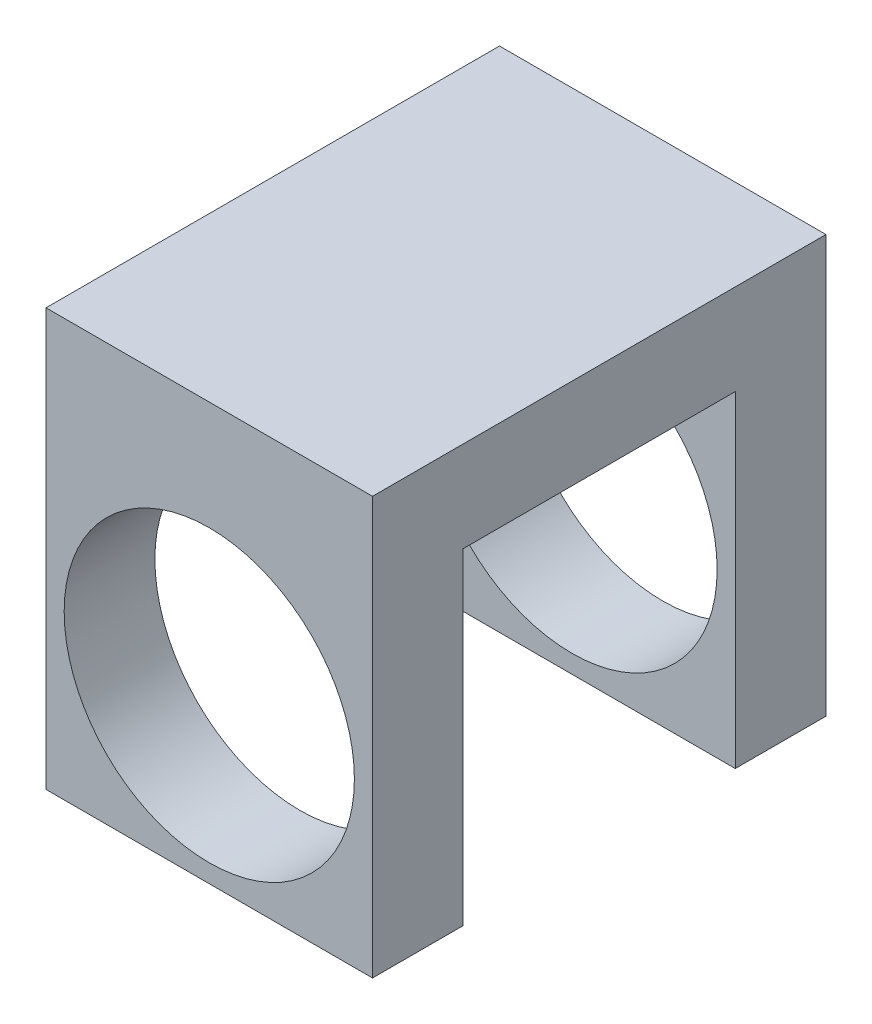
SolidWorks part; units mm, degrees
ref_plane "前视基准面" through (0, 0, 0) normal (0, 0, 1) x (1, 0, 0)
ref_plane "上视基准面" through (0, 0, 0) normal (0, 1, 0) x (1, 0, 0)
ref_plane "右视基准面" through (0, 0, 0) normal (1, 0, 0) x (0, 0, -1)
other "Configuration Table"
sketch "草图1" plane through (0, 0, 0) normal (0, 0, 1) x (1, 0, 0)
  line L1 (-9, -9) -> (9, -9)
  line L2 (-9, -9) -> (-9, 9)
  line L3 (-9, 9) -> (9, 9)
  line L4 (9, -9) -> (9, 9)
  line L5 (-9, -9) -> (9, 9) construction
  line L6 (-9, 9) -> (9, -9) construction
  point P0 (0, 0)
  dimension "D1" = 18
  dimension "D2" = 18
extrude "凸台-拉伸1" add sketch "草图1" along normal blind 5
sketch "草图2" plane through (0, 0, 5) normal (0, 0, 1) x (1, 0, 0)
  circle A0 centre (0, 0) radius 8
  dimension "D1" = 16
extrude "切除-拉伸1" cut sketch "草图2" against normal blind 5
sketch "草图3" plane through (0, 9, 0) normal (0, 1, 0) x (1, 0, 0)
  line L0 (9, -5) -> (9, 0) construction
  line L1 (-9, -5) -> (9, -5)
  line L2 (-9, -5) -> (-9, 20)
  line L3 (-9, 20) -> (9, 20)
  line L4 (9, -5) -> (9, 20)
  dimension "D1" = 0
  dimension "D2" = 25
extrude "凸台-拉伸2" add sketch "草图3" along normal blind 5
sketch "草图4" plane through (0, 9, 0) normal (0, -1, 0) x (1, 0, 0)
  line L0 (9, 0) -> (9, -20) construction
  line L1 (-9, -20) -> (9, -20)
  line L2 (-9, -20) -> (-9, -15)
  line L3 (-9, -15) -> (9, -15)
  line L4 (9, -20) -> (9, -15)
  dimension "D1" = 5
extrude "凸台-拉伸3" add sketch "草图4" along normal blind 18
sketch "草图5" plane through (0, 0, -15) normal (0, 0, 1) x (1, 0, 0)
  circle A0 centre (0, 0) radius 8
extrude "切除-拉伸2" cut sketch "草图5" against normal blind 18
sketch "草图6" plane through (0, 14, 0) normal (0, 1, 0) x (1, 0, 0)
  line L0 (-9, 20) -> (9, -5)
  line L1 (9, 20) -> (-9, -5)
